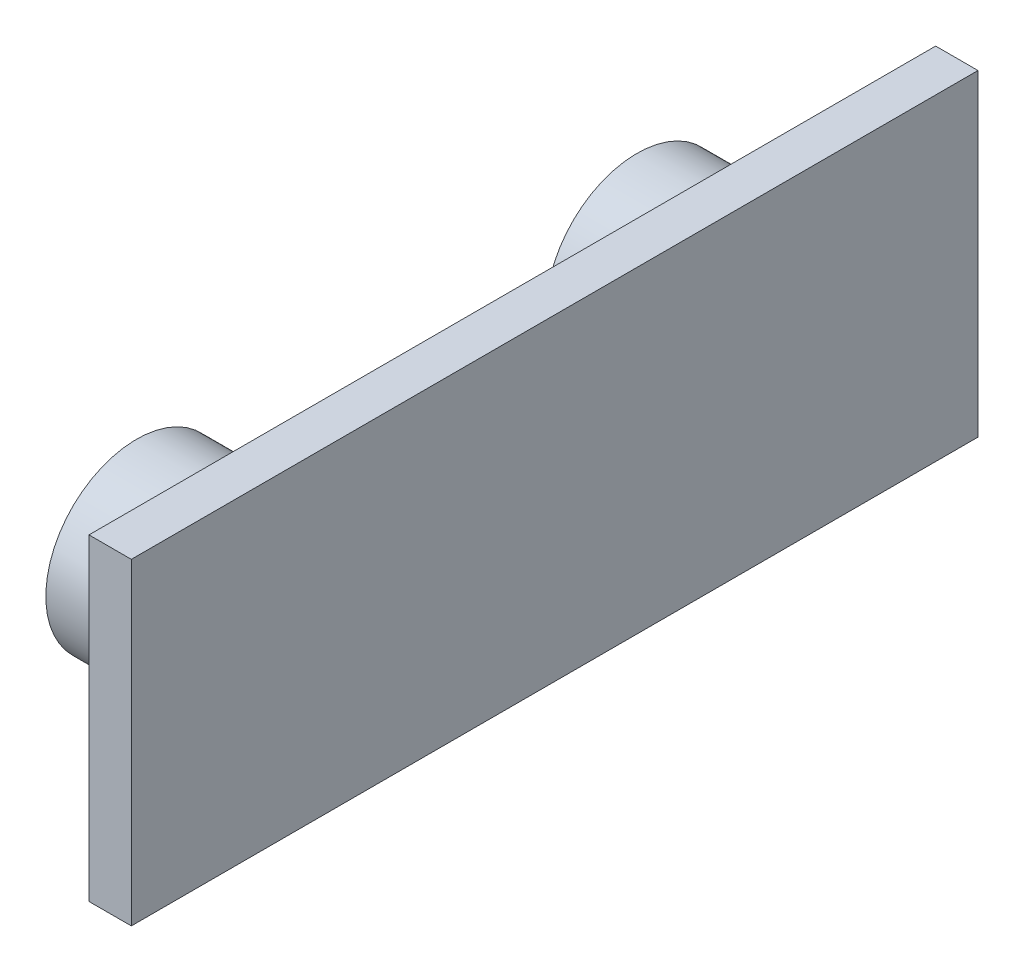
SolidWorks part; units mm, degrees
ref_plane "Front Plane" through (0, 0, 0) normal (0, 0, 1) x (1, 0, 0)
ref_plane "Top Plane" through (0, 0, 0) normal (0, 1, 0) x (1, 0, 0)
ref_plane "Right Plane" through (0, 0, 0) normal (1, 0, 0) x (0, 0, -1)
sketch "Sketch1" plane through (0, 0, 0) normal (1, 0, 0) x (0, 0, -1)
  line L1 (20, -7.5) -> (-20, -7.5)
  line L2 (20, -7.5) -> (20, 7.5)
  line L3 (20, 7.5) -> (-20, 7.5)
  line L4 (-20, -7.5) -> (-20, 7.5)
  line L5 (20, -7.5) -> (-20, 7.5) construction
  line L6 (20, 7.5) -> (-20, -7.5) construction
  circle A0 centre (-11.7476, 0) radius 4.2917
  circle A1 centre (11.8913, -0.1243) radius 4.2917
  point P0 (0, 0)
  dimension "D1" = 40
  dimension "D2" = 15
extrude "Boss-Extrude1" add sketch "Sketch1" along normal blind 2
sketch "Sketch2" plane through (2, 0, 0) normal (1, 0, 0) x (0, 0, -1)
  circle A0 centre (-11.7476, 0) radius 4.2917
  circle A1 centre (-11.7476, 0) radius 4.2917 construction
  circle A2 centre (11.8913, -0.1243) radius 4.2917
extrude "Boss-Extrude2" add sketch "Sketch2" against normal blind 8
